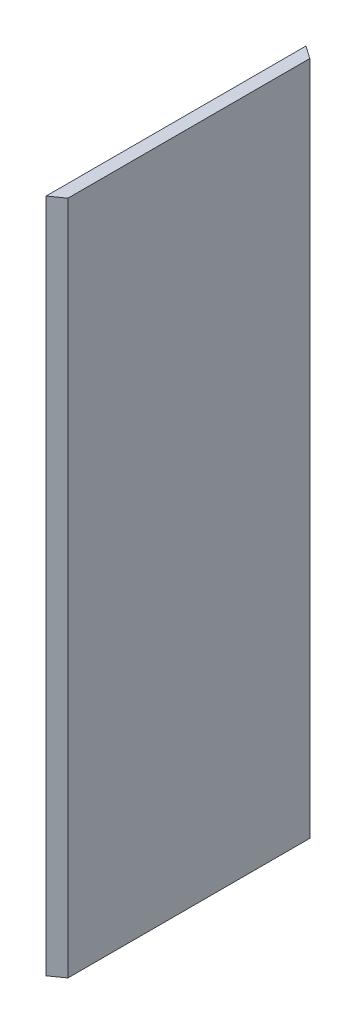
SolidWorks part; units mm, degrees
ref_plane "Front Plane" through (0, 0, 0) normal (0, 0, 1) x (1, 0, 0)
ref_plane "Top Plane" through (0, 0, 0) normal (0, 1, 0) x (1, 0, 0)
ref_plane "Right Plane" through (0, 0, 0) normal (1, 0, 0) x (0, 0, -1)
sketch "Sketch1" plane through (0, 0, 0) normal (0, 1, 0) x (1, 0, 0)
  line L9 (0, 0) -> (0, 5)
  line L10 (0, 5) -> (0.2457, 4.8279)
  line L11 (0.2457, 4.8279) -> (0.2457, 0.1721)
  line L12 (0.2457, 0.1721) -> (0, 0)
  dimension "D1" = 55
  dimension "D2" = 55
  dimension "D4" = 5
  dimension "D3" = 0.3
extrude "Boss-Extrude1" add sketch "Sketch1" along normal blind 13
equation "\"t\"= 0.3'thickness of the sheets"
equation "\"FlexJoint\"= 0.15'Width of flextures"
equation "\"FoldJoint\"= 0.4'Width of folding joints"
equation "\"AssembleAngle\"= 90'Angle of assembly parts"
equation "\"D1@Boss-Extrude1\"=\"t\""
equation "\"D3@Sketch1\"=\"t\""
